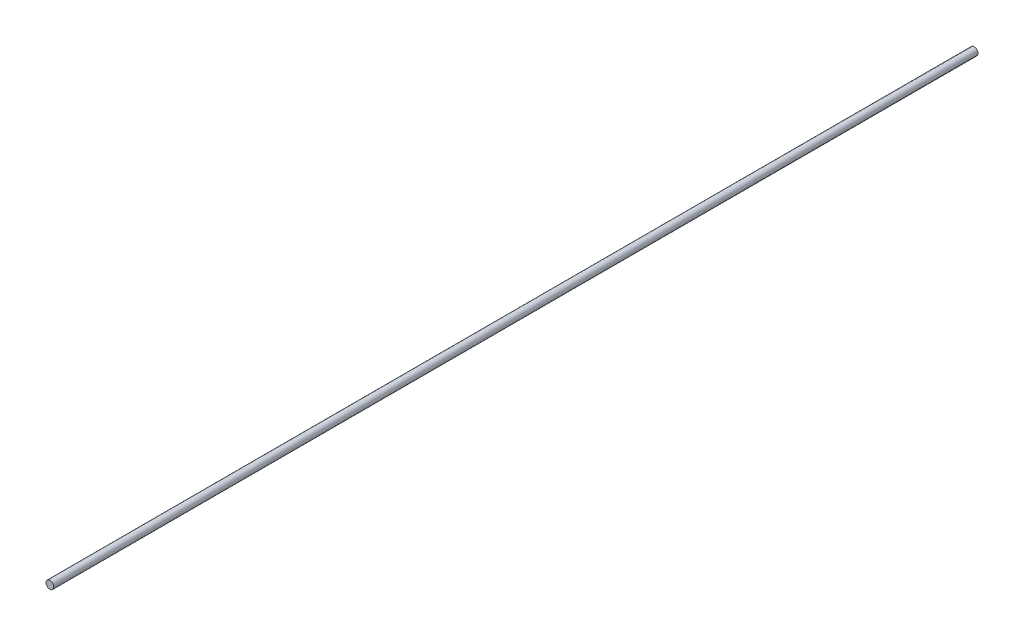
SolidWorks part; units mm, degrees
ref_plane "Front Plane" through (0, 0, 0) normal (0, 0, 1) x (1, 0, 0)
ref_plane "Top Plane" through (0, 0, 0) normal (0, 1, 0) x (1, 0, 0)
ref_plane "Right Plane" through (0, 0, 0) normal (1, 0, 0) x (0, 0, -1)
sketch "Sketch1" plane through (0, 0, 0) normal (0, 0, 1) x (1, 0, 0)
  circle A0 centre (0, 0) radius 6.35
  dimension "D1" = 12.7
extrude "Boss-Extrude1" add sketch "Sketch1" along normal mid plane 1524
